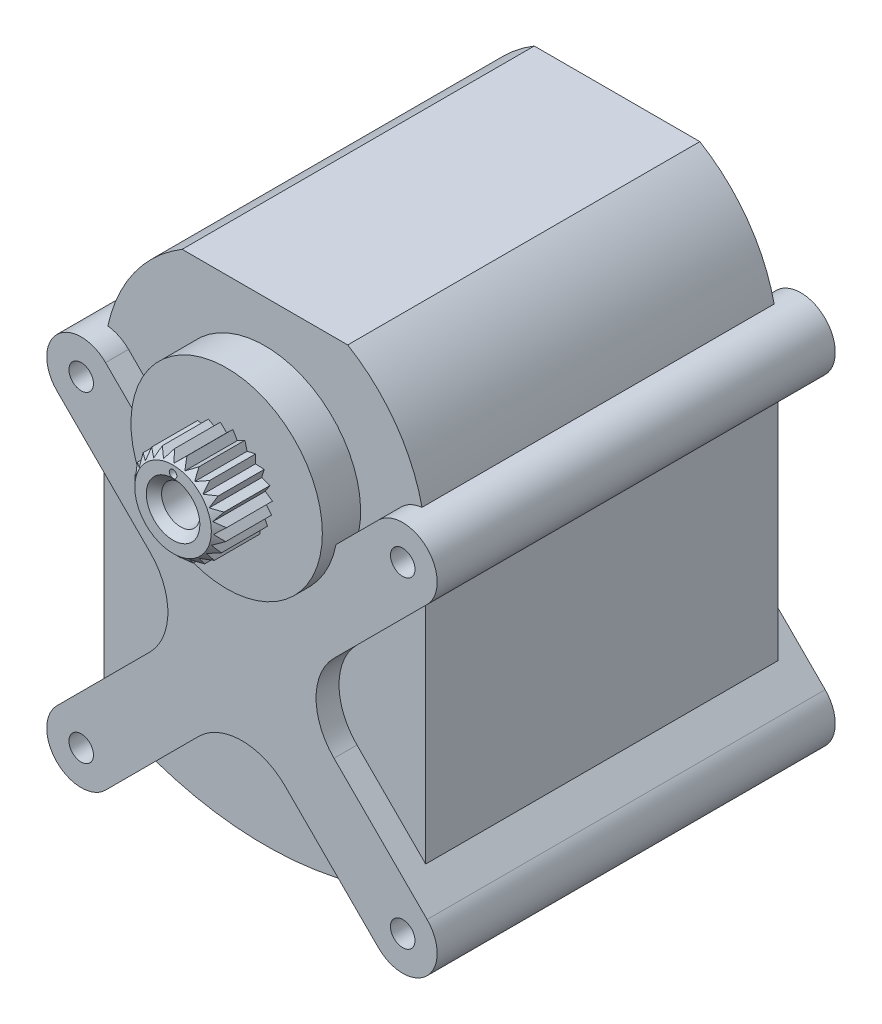
SolidWorks part; units mm, degrees
material "ABS"
ref_plane "Front" through (0, 0, 0) normal (0, 0, 1) x (1, 0, 0)
ref_plane "Top" through (0, 0, 0) normal (0, 1, 0) x (1, 0, 0)
ref_plane "Right" through (0, 0, 0) normal (1, 0, 0) x (0, 0, -1)
sketch "ｽｹｯﾁ1" plane through (0, 0, 0) normal (0, 0, 1) x (1, 0, 0)
  line L0 (-5.4083, 9) -> (5.4083, 9)
  line L1 (-10.5, -19.3326) -> (-10.5, 0)
  line L2 (-10.5, 0) -> (10.5, 0) construction
  line L3 (10.5, 0) -> (10.5, -19.3326)
  arc A0 (-5.4083, 9) -> (-10.5, 0) centre (0, 0) ccw
  arc A1 (-10.5, -19.3326) -> (10.5, -19.3326) centre (0, 0) ccw
  arc A2 (10.5, 0) -> (5.4083, 9) centre (0, 0) ccw
  dimension "D1" = 21
  dimension "D3" = 44
  dimension "D2" = 9
  dimension "D4" = 21
extrude "ﾎﾞｽ - 押し出し1" add sketch "ｽｹｯﾁ1" along normal mid plane 23
sketch "ｽｹｯﾁ8" plane through (0, 0, 0) normal (1, 0, 0) x (0, 0, -1)
  line L0 (0, -10.5) -> (11.5, -10.5) construction
  line L1 (0, 0) -> (0, -10.5) construction
  line L2 (-11.5, 0) -> (11.5, 0) construction
  line L3 (11.5, -19.3326) -> (11.5, 0) construction
  dimension "D1" = 10.5
sketch "ｽｹｯﾁ2" plane through (0, 0, 0) normal (0, 0, 1) x (1, 0, 0)
  circle A0 centre (0, 0) radius 6.25
  dimension "D1" = 12.5
extrude "ﾎﾞｽ - 押し出し2" add sketch "ｽｹｯﾁ2" along normal mid plane 28
sketch "ｽｹｯﾁ3" plane through (0, 0, -14) normal (0, 0, -1) x (-1, 0, 0)
  circle A0 centre (0, 0) radius 3.5
  dimension "D1" = 7
extrude "ﾎﾞｽ - 押し出し3" add sketch "ｽｹｯﾁ3" along normal blind 2
chamfer "面取り1" distance 0.5 angle 45 1 edges at (-3.5, 0, -16)
hole_wizard "M2.5x0.45 ねじ穴1" positions "ｽｹｯﾁ4" profile "ｽｹｯﾁ6" tap size "M2.5x0.45" standard "JIS"
sketch "ｽｹｯﾁ4" plane through (0, 0, -16) normal (0, 0, -1) x (-1, 0, 0)
  point P0 (0, 0)
sketch "ｽｹｯﾁ6" plane through (0, 0, -16) normal (1, 0, 0) x (0, 1, 0)
  line L0 (0, 0) -> (0, 7.8659)
  line L1 (0, 7.8659) -> (1.025, 7.25)
  line L2 (1.025, 7.25) -> (1.025, 0)
  line L5 (1.025, 0) -> (0, 0)
  line L10 (0, 7.8659) -> (-1.025, 7.25) construction
  line L11 (0, -6.35) -> (0, 107.95) construction
  dimension "ねじ下穴ﾄﾞﾘﾙ直径" = 2.05
  dimension "ねじ下穴ﾄﾞﾘﾙの深さ" = 7.25
  dimension "ﾄﾞﾘﾙ角度" = 118
cosmetic thread "穴のねじ山1" parameters "D1"=5, "D2"=2.5
sketch "ｽｹｯﾁ7" plane through (0, 0, 0) normal (0, 0, 1) x (1, 0, 0)
  line L0 (0, 0) -> (0, -10.5) construction
  line L1 (0, -10.5) -> (-10.5, 0) construction
  line L2 (0, 0) -> (-10.5, 0) construction
  line L3 (-12.091, -1.591) -> (-3.182, -10.5)
  line L4 (-3.182, -10.5) -> (0, -10.5)
  line L5 (0, -10.5) -> (0, -7.318)
  line L6 (0, -7.318) -> (-8.909, 1.591)
  arc A0 (-8.909, 1.591) -> (-12.091, -1.591) centre (-10.5, 0) ccw
  dimension "D1" = 4.5
extrude "ﾎﾞｽ - 押し出し4" add sketch "ｽｹｯﾁ7" along normal mid plane 26
hole_wizard "M2x0.4 ねじ穴1" positions "ｽｹｯﾁ9" profile "ｽｹｯﾁ11" tap size "M2x0.4" standard "JIS" end condition through all
sketch "ｽｹｯﾁ9" plane through (0, 0, 13) normal (0, 0, 1) x (1, 0, 0)
  point P0 (-10.5, 0)
sketch "ｽｹｯﾁ11" plane through (-10.5, 0, 13) normal (1, 0, 0) x (0, -1, 0)
  line L0 (0, 0) -> (0, 29)
  line L1 (0, 29) -> (0.8, 29)
  line L2 (0.8, 29) -> (0.8, 0)
  line L5 (0.8, 0) -> (0, 0)
  line L11 (0, -6.35) -> (0, 107.95) construction
  dimension "次ｻｰﾌｪｽまでのねじ下穴ﾄﾞﾘﾙ直径" = 1.6
  dimension "次ｻｰﾌｪｽまでのねじ下穴ﾄﾞﾘﾙの深さ" = 29
cosmetic thread "穴のねじ山2" parameters "D2"=2
pattern_circular "円形ﾊﾟﾀｰﾝ1" count 4 over 360 about axis through (0, -10.5, 0) along (0, 0, 1) of "ﾎﾞｽ - 押し出し4", "M2x0.4 ねじ穴1"
cosmetic thread "穴のねじ山3" parameters "D2"=2
cosmetic thread "穴のねじ山4" parameters "D2"=2
cosmetic thread "穴のねじ山5" parameters "D2"=2
fillet "ﾌｨﾚｯﾄ1" radius 4 6 edges at (-3.182, -10.5, -12.25) (-3.182, -10.5, 12.25) (0, -13.682, -12.25) (0, -13.682, 12.25) (3.182, -10.5, -12.25) (3.182, -10.5, 12.25)
sketch "ｽｹｯﾁ12" plane through (0, 0, -13) normal (0, 0, -1) x (-1, 0, 0)
  line L0 (0, -7.318) -> (-1.1805, -6.1375)
  line L1 (-1.1805, -6.1375) -> (1.1805, -6.1375)
  line L2 (1.1805, -6.1375) -> (0, -7.318)
extrude "ﾎﾞｽ - 押し出し5" add sketch "ｽｹｯﾁ12" against normal up to surface (26 mm away) up to face at (-9.7, -21, 13)
ref_plane "平面1" through (0, 0, 17.5) normal (0, 0, 1) x (1, 0, 0)
sketch "ｽｹｯﾁ13" plane through (0, 0, 14) normal (0, 0, 1) x (1, 0, 0)
  circle A0 centre (0, 0) radius 3
  dimension "D1" = 6
extrude "ﾎﾞｽ - 押し出し6" add sketch "ｽｹｯﾁ13" along normal up to surface (3.5 mm away) up to plane "平面1"
hole_wizard "M3x0.5 ねじ穴1" positions "ｽｹｯﾁ14" profile "ｽｹｯﾁ16" tap size "M3x0.5" standard "JIS"
sketch "ｽｹｯﾁ14" plane through (0, 0, 17.5) normal (0, 0, 1) x (1, 0, 0)
  point P0 (0, 0)
sketch "ｽｹｯﾁ16" plane through (0, 0, 17.5) normal (1, 0, 0) x (0, -1, 0)
  line L0 (0, 0) -> (0, 10.7511)
  line L1 (0, 10.7511) -> (1.25, 10)
  line L2 (1.25, 10) -> (1.25, 0)
  line L5 (1.25, 0) -> (0, 0)
  line L10 (0, 10.7511) -> (-1.25, 10) construction
  line L11 (0, -6.35) -> (0, 107.95) construction
  dimension "ねじ下穴ﾄﾞﾘﾙ直径" = 2.5
  dimension "ねじ下穴ﾄﾞﾘﾙの深さ" = 10
  dimension "ﾄﾞﾘﾙ角度" = 118
cosmetic thread "穴のねじ山6" parameters "D1"=6, "D2"=3
chamfer "面取り2" distance 0.5 angle 45 2 edges at (1.25, 0, 17.5) (3, 0, 17.5)
sketch "ｽｹｯﾁ17" plane through (0, 0, 17.5) normal (0, 0, 1) x (1, 0, 0)
  line L0 (0, 2) -> (0, 0) construction
  circle A0 centre (0, 2) radius 0.25
  dimension "D2" = 0.5
  dimension "D1" = 2
extrude "ｶｯﾄ - 押し出し1" cut sketch "ｽｹｯﾁ17" against normal blind 0.5
sketch "ｽｹｯﾁ18" plane through (0, 0, 17.5) normal (0, 0, 1) x (1, 0, 0)
  line L0 (0, 0) -> (0, 2.5745) construction
  line L1 (0, 2.5745) -> (-0.4085, 2.9721)
  line L3 (0.4085, 2.9721) -> (0, 0) construction
  line L4 (-0.4085, 2.9721) -> (0, 0) construction
  line L5 (0, 2.5745) -> (0.4085, 2.9721)
  line L6 (-0.4085, 2.9721) -> (-0.4766, 3.4674)
  line L7 (0.4085, 2.9721) -> (0.4766, 3.4674)
  circle A0 centre (0, 0) radius 3 construction
  circle A1 centre (0, 0) radius 3 construction
  arc A2 (-0.4085, 2.9721) -> (0.4085, 2.9721) centre (0, 0) cw construction
  arc A3 (-0.4766, 3.4674) -> (0.4766, 3.4674) centre (0, 0) cw
  dimension "D1" = 15.652
  dimension "D2" = 0.57
  dimension "D3" = 0.5
extrude "ｶｯﾄ - 押し出し2" cut sketch "ｽｹｯﾁ18" against normal up to surface (3.5 mm away) up to face at (3, 0, 14)
pattern_circular "円形ﾊﾟﾀｰﾝ2" count 23 over 360 about axis through (0, 0, 0) along (0, 0, 1) of "ｶｯﾄ - 押し出し2"
